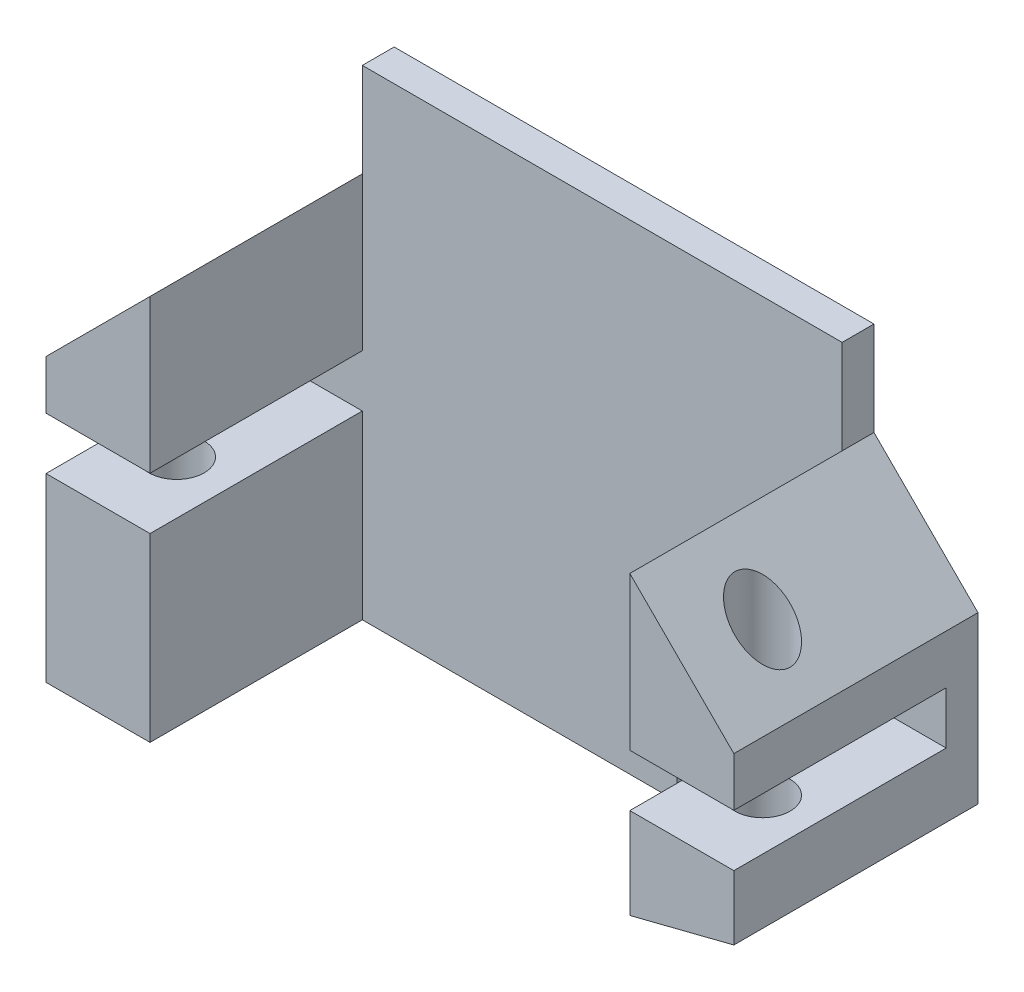
SolidWorks part; units mm, degrees
ref_plane "前视基准面" through (0, 0, 0) normal (0, 0, 1) x (1, 0, 0)
ref_plane "上视基准面" through (0, 0, 0) normal (0, 1, 0) x (1, 0, 0)
ref_plane "右视基准面" through (0, 0, 0) normal (1, 0, 0) x (0, 0, -1)
sketch "草图1" plane through (0, 0, 0) normal (0, 0, 1) x (1, 0, 0)
  line L5 (-16.5627, 3.0348) -> (-16.5627, 29.1923) construction
  line L6 (15.8373, 3.0348) -> (15.8373, 26.0998) construction
  line L8 (-16.5627, -12.8666) -> (15.8373, -12.8666)
  line L9 (-16.5627, -12.8666) -> (-16.5627, 17.1334)
  line L10 (-16.5627, 17.1334) -> (15.8373, 17.1334)
  line L11 (15.8373, -12.8666) -> (15.8373, 17.1334)
extrude "凸台-拉伸1" add sketch "草图1" along normal blind 1.5
sketch "草图2" plane through (0, 0, 1.5) normal (0, 0, 1) x (1, 0, 0)
  line L0 (-16.5627, 17.1334) -> (-16.5627, -12.8666) construction
  line L1 (-16.5627, 3.0348) -> (-11.6627, 3.0348)
  line L2 (-16.5627, 3.0348) -> (-16.5627, -5.4852)
  line L5 (-16.5627, 3.0348) -> (-11.6627, 3.0348) construction
  line L6 (-16.5627, 5.4948) -> (-11.6627, 5.4948)
  line L7 (-11.6627, 5.4948) -> (-16.5627, 5.4948) construction
  line L8 (-11.6627, 5.4948) -> (-11.6627, 12.7081)
  line L9 (-11.6627, 21.7548) -> (-11.6627, 5.4948) construction
  line L11 (-11.6627, 12.7081) -> (-16.5627, 7.8081)
  line L12 (-16.5627, 7.8081) -> (-16.5627, 5.4948)
  line L13 (10.9373, 5.4948) -> (10.9373, 12.7081)
  line L14 (10.9373, 5.4948) -> (10.9373, 21.7548) construction
  line L15 (10.9373, 12.7081) -> (15.8373, 7.8081)
  line L16 (15.8373, -12.8666) -> (15.8373, 17.1334) construction
  line L17 (15.8373, 7.8081) -> (15.8373, 5.4948)
  line L18 (15.8373, 5.4948) -> (10.9373, 5.4948) construction
  line L19 (15.8373, 5.4948) -> (10.9373, 5.4948)
  line L20 (10.9373, 3.0348) -> (15.8373, 3.0348)
  line L21 (10.9373, 3.0348) -> (15.8373, 3.0348) construction
  line L22 (15.8373, 3.0348) -> (15.8373, 0)
  line L23 (15.8373, 0) -> (10.9373, -1.2452)
  line L24 (10.9373, -1.2452) -> (10.9373, 3.0348)
  line L25 (-16.5627, -5.4852) -> (-11.6627, -5.4852)
  line L26 (-11.6627, -5.4852) -> (-11.6627, 3.0348)
extrude "凸台-拉伸2" add sketch "草图2" along normal blind 10
sketch "草图3" plane through (0, 0, 1.5) normal (0, 0, 1) x (1, 0, 0)
  line L0 (-16.5627, 7.8081) -> (-11.6627, 12.7081)
  line L1 (-11.6627, 12.7081) -> (-11.6627, 17.1334)
  line L2 (15.8373, 17.1334) -> (-16.5627, 17.1334) construction
  line L3 (-11.6627, 21.7548) -> (-11.6627, 5.4948) construction
  line L4 (-11.6627, 17.1334) -> (-16.5627, 17.1334)
  line L5 (-16.5627, 17.1334) -> (-16.5627, 7.8081)
  line L6 (15.8373, 7.8081) -> (10.9373, 12.7081)
  line L7 (10.9373, 12.7081) -> (10.9373, 17.1334)
  line L8 (10.9373, 5.4948) -> (10.9373, 21.7548) construction
  line L9 (10.9373, 17.1334) -> (15.8373, 17.1334)
  line L10 (15.8373, 17.1334) -> (15.8373, 7.8081)
  line L11 (-16.5627, -12.8666) -> (-16.5627, -8.702)
  line L12 (-16.5627, -5.4852) -> (-16.5627, -12.8666) construction
  line L13 (-16.5627, -8.702) -> (-16.5627, -5.4852)
  line L14 (-16.5627, -5.4852) -> (3.1573, -5.4852)
  line L15 (3.1573, -5.4852) -> (3.1573, -1.2452)
  line L16 (3.1573, -1.2452) -> (10.9373, -1.2452)
  line L17 (10.9373, -1.2452) -> (15.8373, 0)
  line L18 (15.8373, 0) -> (15.8373, -12.8666)
  line L19 (15.8373, -12.8666) -> (-16.5627, -12.8666)
extrude "切除-拉伸1" cut sketch "草图3" against normal blind 11.5
sketch "草图4" plane through (0, -5.4852, 0) normal (0, -1, 0) x (1, 0, 0)
  circle A0 centre (-14.1627, 7.75) radius 1.3
  circle A1 centre (13.4373, 7.75) radius 1.3
extrude "切除-拉伸2" cut sketch "草图4" against normal blind 31.5
